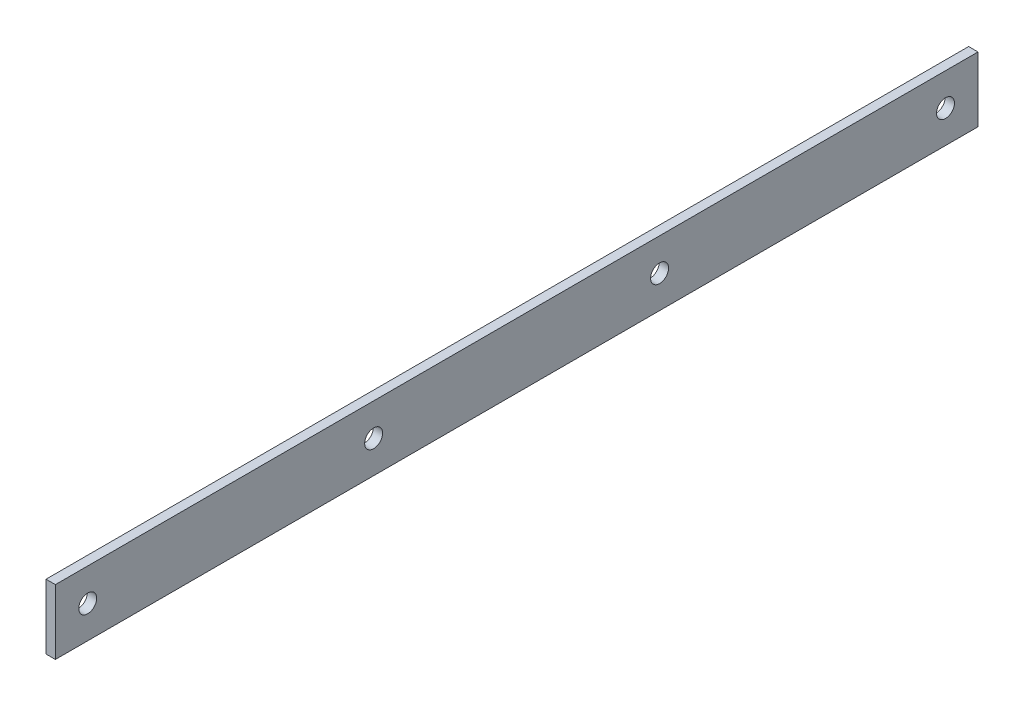
SolidWorks part; units mm, degrees
material "ASTM A36 Steel"
ref_plane "Front Plane" through (0, 0, 0) normal (0, 0, 1) x (1, 0, 0)
ref_plane "Top Plane" through (0, 0, 0) normal (0, 1, 0) x (1, 0, 0)
ref_plane "Right Plane" through (0, 0, 0) normal (1, 0, 0) x (0, 0, -1)
sketch "Sketch1" plane through (0, 0, 0) normal (1, 0, 0) x (0, 0, -1)
  line L1 (-590.5, -41.5) -> (590.5, -41.5)
  line L2 (-590.5, -41.5) -> (-590.5, 41.5)
  line L3 (-590.5, 41.5) -> (590.5, 41.5)
  line L4 (590.5, -41.5) -> (590.5, 41.5)
  line L5 (-590.5, -41.5) -> (590.5, 41.5) construction
  line L6 (-590.5, 41.5) -> (590.5, -41.5) construction
  point P0 (0, 0)
  dimension "D1" = 1181
  dimension "D2" = 83
extrude "Boss-Extrude1" add sketch "Sketch1" along normal blind 12
sketch "Sketch2" plane through (12, 0, 0) normal (1, 0, 0) x (0, 0, -1)
  line L0 (-590.5, 41.5) -> (-590.5, -41.5) construction
  circle A0 centre (-549.1, 0) radius 11.5
  dimension "D1" = 23
  dimension "D2" = 41.4
extrude "Cut-Extrude1" cut sketch "Sketch2" against normal blind 12
pattern_linear "LPattern1" count 4 spacing 366 along (0, 0, -1) of "Cut-Extrude1"
